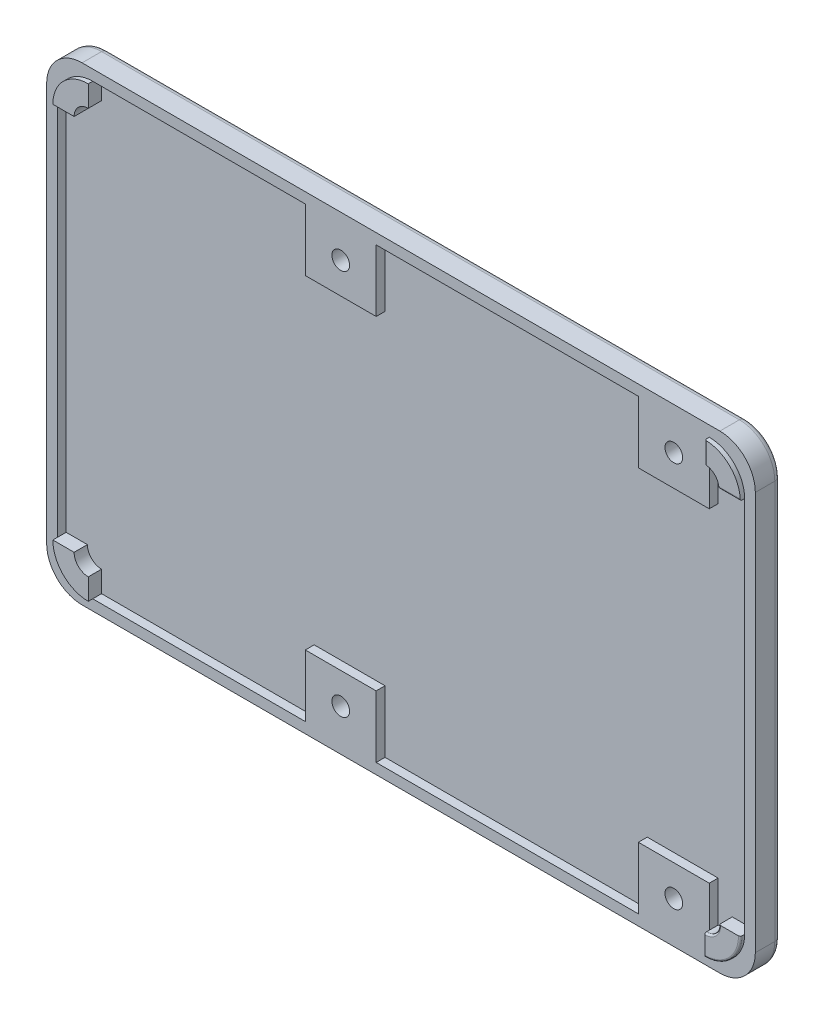
SolidWorks part; units mm, degrees
ref_plane "Plan de face" through (0, 0, 0) normal (0, 0, 1) x (1, 0, 0)
ref_plane "Plan de dessus" through (0, 0, 0) normal (0, 1, 0) x (1, 0, 0)
ref_plane "Plan de droite" through (0, 0, 0) normal (1, 0, 0) x (0, 0, -1)
sketch "Esquisse4" plane through (0, 0, 0) normal (0, 0, 1) x (1, 0, 0)
  line L1 (-40, -26.5) -> (40, -26.5)
  line L2 (-40, -26.5) -> (-40, 26.5)
  line L3 (-40, 26.5) -> (40, 26.5)
  line L4 (40, -26.5) -> (40, 26.5)
  line L5 (-40, -26.5) -> (40, 26.5) construction
  line L6 (-40, 26.5) -> (40, -26.5) construction
  point P0 (0, 0)
  dimension "D1" = 80
  dimension "D2" = 53
extrude "Boss.-Extru.1" add sketch "Esquisse4" along normal blind 2.9
sketch "Esquisse6" plane through (0, 0, 2.9) normal (0, 0, 1) x (1, 0, 0)
  line L1 (-38.8, -25.3) -> (38.8, -25.3)
  line L2 (-38.8, -25.3) -> (-38.8, 25.3)
  line L3 (-38.8, 25.3) -> (38.8, 25.3)
  line L4 (38.8, -25.3) -> (38.8, 25.3)
  line L5 (-38.8, -25.3) -> (38.8, 25.3) construction
  line L6 (-38.8, 25.3) -> (38.8, -25.3) construction
  point P0 (0, 0)
  dimension "D1" = 77.6
  dimension "D2" = 50.6
extrude "Enlèv. mat.-Extru.1" cut sketch "Esquisse6" against normal blind 1
fillet "Congé1" radius 4 8 edges at (38.8, -25.3, 2.4) (38.8, 25.3, 2.4) (-38.8, 25.3, 2.4) (-38.8, -25.3, 2.4) (-40, -26.5, 1.45) (40, -26.5, 1.45) (40, 26.5, 1.45) (-40, 26.5, 1.45)
fillet "Congé2" radius 0.7 8 edges at (38.8284, 25.3284, 0) (40, 0, 0) (38.8284, -25.3284, 0) (0, -26.5, 0) (-38.8284, -25.3284, 0) (-40, 0, 0) (-38.8284, 25.3284, 0) (0, 26.5, 0)
sketch "Esquisse8" plane through (0, 0, 1.9) normal (0, 0, 1) x (1, 0, 0)
  line L0 (-34.8, 25.3) -> (-34.8, 22.9) construction
  line L1 (-38.8, 21.3) -> (-36.4, 21.3) construction
  line L2 (-36.4, 21.3) -> (-38.8, 21.3)
  line L3 (-34.8, 22.9) -> (-34.8, 25.3)
  arc A0 (-34.8, 22.9) -> (-36.4, 21.3) centre (-34.8, 21.3) ccw
  arc A1 (-34.8, 25.3) -> (-38.8, 21.3) centre (-34.8, 21.3) ccw
  dimension "D1" = 2.4
  dimension "D2" = 2.4
extrude "Boss.-Extru.2" add sketch "Esquisse8" along normal blind 1.5
mirror "Symétrie1" about plane through (0, 0, 0) normal (1, 0, 0) of "Boss.-Extru.2" second plane through (0, 0, 0) second plane normal (0, 1, 0)
sketch "Esquisse10" plane through (0, 0, 1.9) normal (0, 0, 1) x (1, 0, 0)
  line L0 (0, 0) -> (-6.8, 0) construction
  line L1 (-6.8, 0) -> (-6.8, 21.8) construction
  dimension "D1" = 6.8
  dimension "D2" = 21.8
sketch "Esquisse11" plane through (0, 0, 1.9) normal (0, 0, 1) x (1, 0, 0)
  line L0 (34.8, 25.3) -> (-34.8, 25.3) construction
  line L1 (-10.8, 18.3) -> (-2.8, 18.3)
  line L2 (-10.8, 18.3) -> (-10.8, 25.3)
  line L3 (-10.8, 25.3) -> (-2.8, 25.3)
  line L4 (-2.8, 18.3) -> (-2.8, 25.3)
  line L5 (-10.8, 18.3) -> (-2.8, 25.3) construction
  line L6 (-10.8, 25.3) -> (-2.8, 18.3) construction
  point P0 (-6.8, 21.8)
  dimension "D1" = 8
extrude "Boss.-Extru.3" add sketch "Esquisse11" along normal blind 1
mirror "Symétrie2" about plane through (0, 0, 0) normal (0, 1, 0) of "Boss.-Extru.3"
sketch "Esquisse12" plane through (0, 0, 2.9) normal (0, 0, 1) x (1, 0, 0)
  line L0 (-10.8, 25.3) -> (-2.8, 18.3) construction
  circle A0 centre (-6.8, 21.8) radius 1
  dimension "D1" = 2
extrude "Enlèv. mat.-Extru.2" cut sketch "Esquisse12" against normal through all
fillet "Congé3" radius 0.2 1 edges at (-5.8, 21.8, 0)
mirror "Symétrie3" about plane through (0, 0, 0) normal (0, 1, 0) of "Congé3", "Enlèv. mat.-Extru.2"
sketch "Esquisse14" plane through (0, 0, 0) normal (0, 0, 1) x (1, 0, 0)
  line L0 (-6.8, 21.8) -> (30.8, 21.8) construction
  dimension "D1" = 37.6
sketch "Esquisse15" plane through (0, 0, 1.9) normal (0, 0, 1) x (1, 0, 0)
  line L0 (34.8, 22.9) -> (34.8, 25.3) construction
  line L1 (26.8, 18.3) -> (34.8, 18.3)
  line L2 (26.8, 18.3) -> (26.8, 25.3)
  line L3 (26.8, 25.3) -> (34.8, 25.3)
  line L4 (34.8, 18.3) -> (34.8, 25.3)
  line L5 (26.8, 18.3) -> (34.8, 25.3) construction
  line L6 (26.8, 25.3) -> (34.8, 18.3) construction
  line L7 (34.8, 25.3) -> (-2.8, 25.3) construction
  point P0 (30.8, 21.8)
extrude "Boss.-Extru.4" add sketch "Esquisse15" along normal blind 1
sketch "Esquisse16" plane through (0, 0, 2.9) normal (0, 0, 1) x (1, 0, 0)
  circle A0 centre (30.8, 21.8) radius 1
  dimension "D1" = 2
extrude "Enlèv. mat.-Extru.3" cut sketch "Esquisse16" against normal through all
fillet "Congé4" radius 0.2 1 edges at (31.8, 21.8, 0)
mirror "Symétrie4" about plane through (0, 0, 0) normal (0, 1, 0) of "Boss.-Extru.4", "Enlèv. mat.-Extru.3", "Congé4"
fillet "Congé5" radius 0.2 3 edges at (37.6, 21.3, 3.4) (37.6284, -24.1284, 3.4) (35.9314, -22.4314, 3.4)
